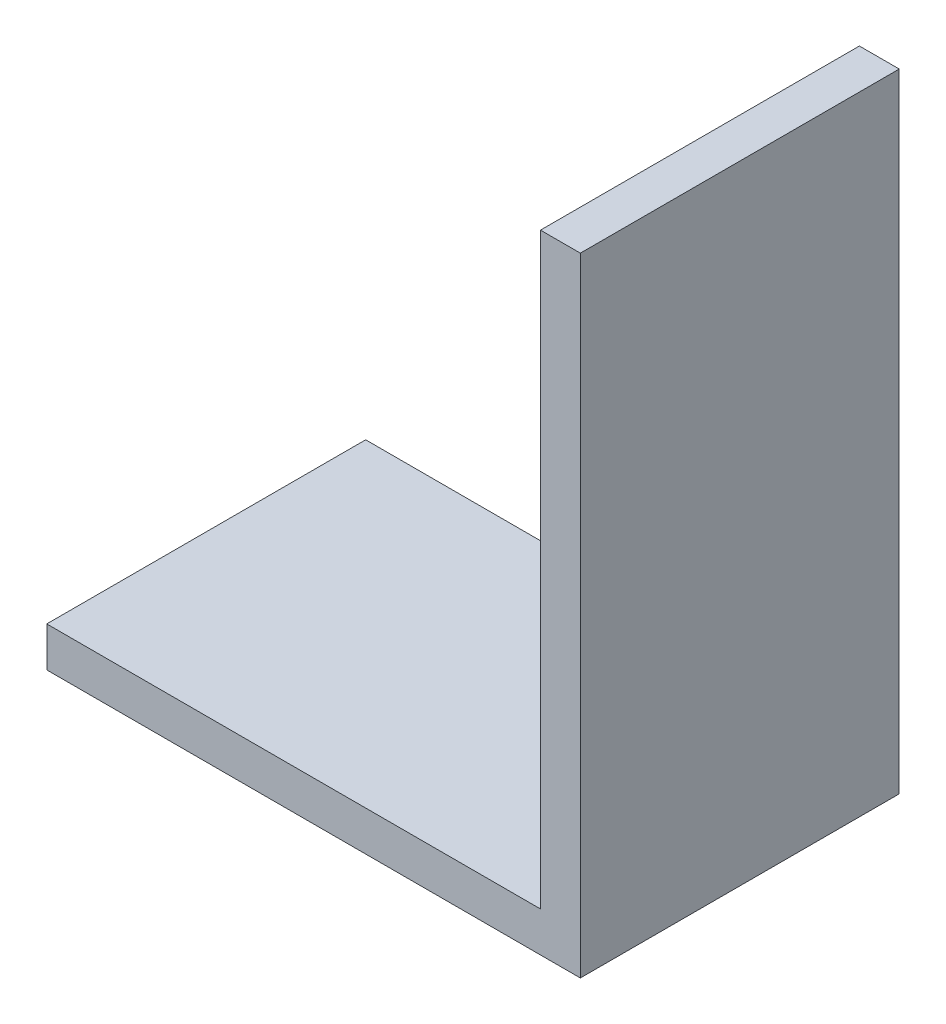
SolidWorks part; units mm, degrees
ref_plane "Front Plane" through (0, 0, 0) normal (0, 0, 1) x (1, 0, 0)
ref_plane "Top Plane" through (0, 0, 0) normal (0, 1, 0) x (1, 0, 0)
ref_plane "Right Plane" through (0, 0, 0) normal (1, 0, 0) x (0, 0, -1)
sketch "Sketch1" plane through (0, 0, 0) normal (0, 0, 1) x (1, 0, 0)
  line L0 (0, 200) -> (0, 0)
  line L1 (0, 0) -> (-170, 0)
  line L2 (-12.7, 200) -> (-12.7, 12.7)
  line L3 (-12.7, 12.7) -> (-170, 12.7)
  line L4 (0, 200) -> (-12.7, 200)
  line L5 (-170, 0) -> (-170, 12.7)
  dimension "D1" = 12.7
  dimension "D2" = 200
  dimension "D3" = 170
extrude "Boss-Extrude1" add sketch "Sketch1" along normal mid plane 101.6
